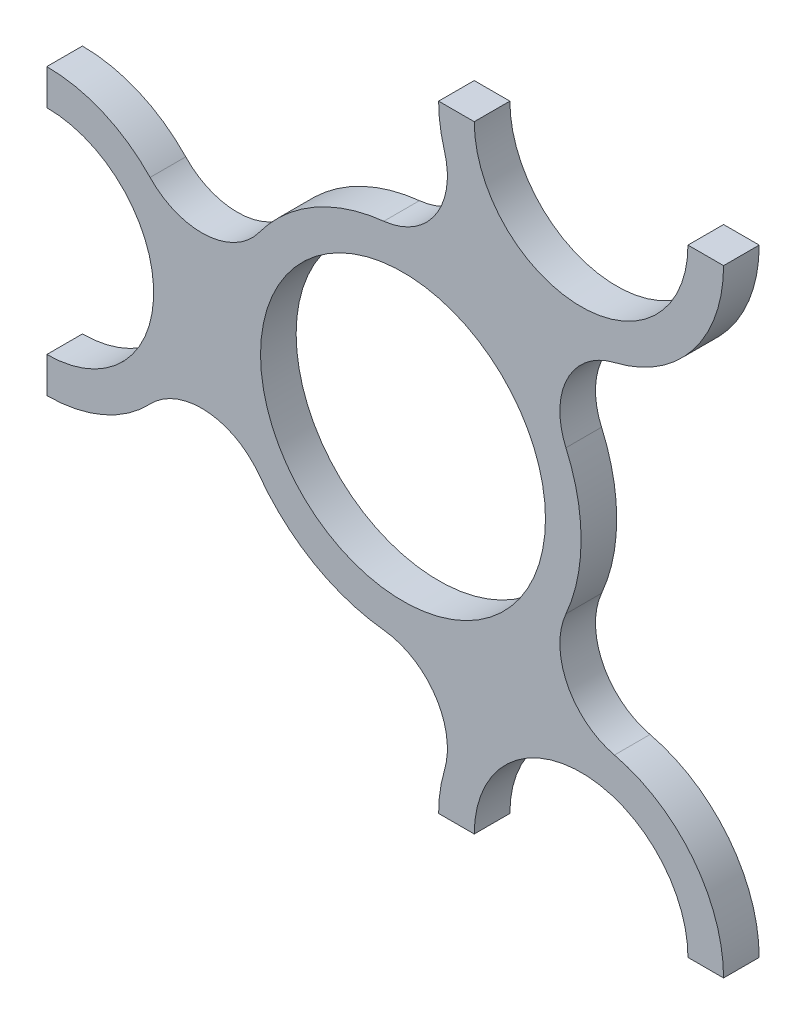
SolidWorks part; units mm, degrees
ref_plane "Front Plane" through (0, 0, 0) normal (0, 0, 1) x (1, 0, 0)
ref_plane "Top Plane" through (0, 0, 0) normal (0, 1, 0) x (1, 0, 0)
ref_plane "Right Plane" through (0, 0, 0) normal (1, 0, 0) x (0, 0, -1)
sketch "Sketch1" plane through (0, 0, 0) normal (0, 0, 1) x (1, 0, 0)
  line L0 (-198.6672, 0) -> (88.1408, 0) construction
  line L1 (-107.3626, 86.6) -> (50.1553, 86.6) construction
  line L2 (-2.6495, 116.5702) -> (-2.6495, -104.7215) construction
  line L3 (-42.6495, 86.6) -> (-32.6495, 86.6)
  line L4 (-52.6495, -104.7215) -> (-52.6495, 125.9795) construction
  line L5 (54.6857, -86.6) -> (-88.5441, -86.6) construction
  line L6 (-152.6495, 125.9795) -> (-152.6495, -104.7215) construction
  line L7 (27.3505, 86.6) -> (37.3505, 86.6)
  line L8 (-42.6495, -86.6) -> (-32.6495, -86.6)
  line L9 (27.3505, -86.6) -> (37.3505, -86.6)
  line L10 (-152.6495, 40) -> (-152.6495, 30)
  line L11 (-152.6495, -30) -> (-152.6495, -40)
  circle A0 centre (-52.6495, 0) radius 40
  arc A1 (-58.0346, 49.7092) -> (-93.0067, 29.5178) centre (-52.6495, 0) ccw
  arc A2 (-32.6495, 86.6) -> (27.3505, 86.6) centre (-2.6495, 86.6) ccw
  arc A3 (6.7101, 47.7104) -> (37.3505, 86.6) centre (-2.6495, 86.6) ccw
  arc A4 (-58.0346, 49.7092) -> (-41.009, 75.2619) centre (-60.1887, 69.5928) ccw
  arc A5 (6.7101, 47.7104) -> (-6.9071, 20.1898) centre (11.3899, 28.2657) ccw
  arc A6 (-42.6495, 86.6) -> (-41.009, 75.2619) centre (-2.6495, 86.6) ccw
  arc A7 (6.7101, -47.7104) -> (37.3505, -86.6) centre (-2.6495, -86.6) cw
  arc A8 (6.7101, -47.7104) -> (-6.9071, -20.1898) centre (11.3899, -28.2657) cw
  arc A9 (-42.6495, -86.6) -> (-41.009, -75.2619) centre (-2.6495, -86.6) cw
  arc A10 (-58.0346, -49.7092) -> (-41.009, -75.2619) centre (-60.1887, -69.5928) cw
  arc A11 (-32.6495, -86.6) -> (27.3505, -86.6) centre (-2.6495, -86.6) cw
  arc A12 (-6.9071, -20.1898) -> (-6.9071, 20.1898) centre (-52.6495, 0) ccw
  arc A13 (-123.6495, 27.55) -> (-152.6495, 40) centre (-152.6495, 0) ccw
  arc A14 (-152.6495, -30) -> (-152.6495, 30) centre (-152.6495, 0) ccw
  arc A15 (-123.6495, 27.55) -> (-93.0067, 29.5178) centre (-109.1495, 41.3249) ccw
  arc A16 (-93.0067, -29.5178) -> (-123.6495, -27.55) centre (-109.1495, -41.3249) ccw
  arc A17 (-93.0067, -29.5178) -> (-58.0346, -49.7092) centre (-52.6495, 0) ccw
  arc A18 (-152.6495, -40) -> (-123.6495, -27.55) centre (-152.6495, 0) ccw
  dimension "D5" = 100
  dimension "D7" = 80
  dimension "D8" = 60
  dimension "D9" = 60
  dimension "D10" = 80
  dimension "D11" = 20
  dimension "D1" = 86.6
  dimension "D2" = 86.6
  dimension "D3" = 50
  dimension "D4" = 100
extrude "Boss-Extrude1" add sketch "Sketch1" along normal blind 10
